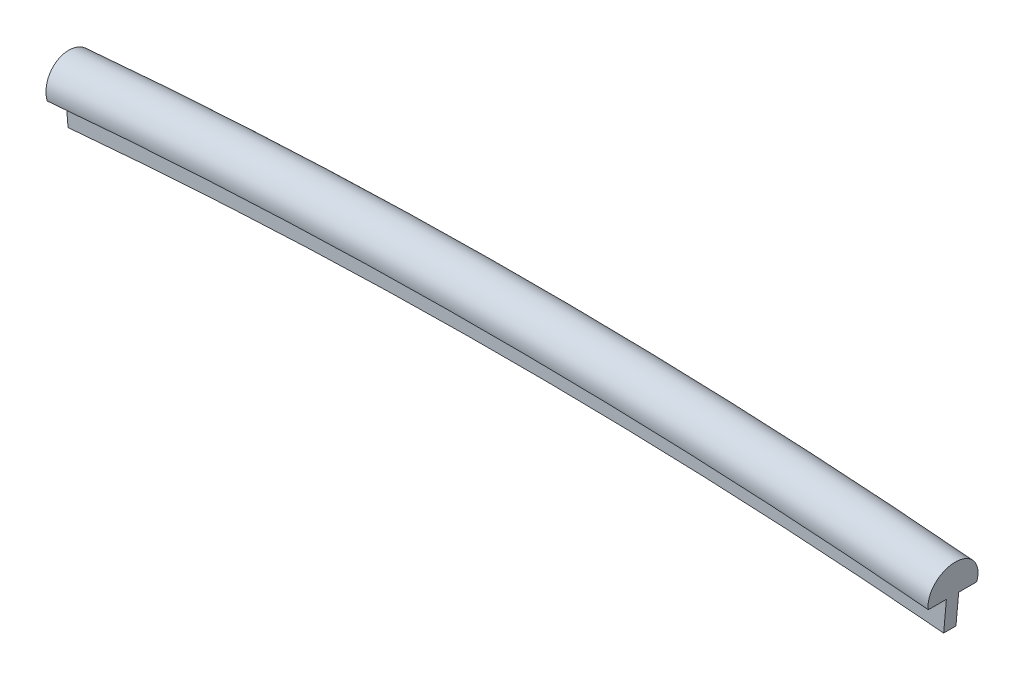
SolidWorks part; units mm, degrees
ref_plane "Front Plane" through (0, 0, 0) normal (0, 0, 1) x (1, 0, 0)
ref_plane "Top Plane" through (0, 0, 0) normal (0, 1, 0) x (1, 0, 0)
ref_plane "Right Plane" through (0, 0, 0) normal (1, 0, 0) x (0, 0, -1)
sketch "Sketch2" plane through (0, 0, 0) normal (1, 0, 0) x (0, 0, -1)
  line L0 (0, 241.3) -> (0, 0) construction
  line L2 (0, 241.3) -> (0, 239.8) construction
  line L3 (0, 239.8) -> (0.3, 239.8)
  line L4 (0, 239.8) -> (-0.3, 239.8)
  line L5 (-0.3, 239.8) -> (-0.3, 241.3)
  line L6 (0.3, 239.8) -> (0.3, 241.3)
  line L7 (0, 241.3) -> (0, 242.8) construction
  line L8 (-1.18, 241.3) -> (-0.3, 241.3)
  line L9 (0.3, 241.3) -> (1.18, 241.3)
  arc A0 (-1.18, 241.3) -> (1.18, 241.3) centre (0, 241.586) cw
  point P14 (0, 241.3)
ref_axis "Axis2" through (0, 0, 70.5976) along (0, 0, -1)
revolve "Revolve1" add sketch "Sketch2" angle 5.115 about axis through (0, 0, 70.5976) along (0, 0, -1)
